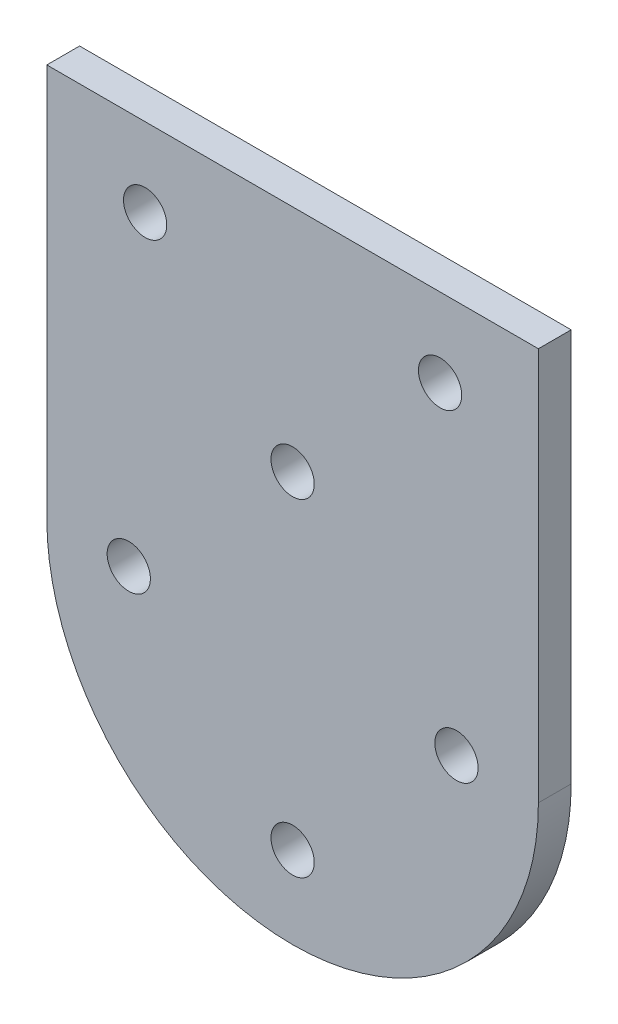
SolidWorks part; units mm, degrees
ref_plane "Front Plane" through (0, 0, 0) normal (0, 0, 1) x (1, 0, 0)
ref_plane "Top Plane" through (0, 0, 0) normal (0, 1, 0) x (1, 0, 0)
ref_plane "Right Plane" through (0, 0, 0) normal (1, 0, 0) x (0, 0, -1)
sketch "Sketch6" plane through (0, 0, 0) normal (0, 0, 1) x (1, 0, 0)
  line L0 (0, 0) -> (62.1656, 0) construction
  line L4 (-62.1656, 0) -> (0, 0) construction
  line L12 (0, -3.292) -> (0, 175) construction
  line L13 (37.5, 0) -> (37.5, 60)
  line L14 (37.5, 60) -> (-37.5, 60)
  line L15 (-37.5, 60) -> (-37.5, 0)
  arc A2 (-37.5, 0) -> (37.5, 0) centre (0, 0) ccw
  arc A7 (-37.5, 0) -> (37.5, 0) centre (0, 0) ccw
  dimension "D4" = 75
  dimension "D5" = 60
extrude "Boss-Extrude1" add sketch "Sketch6" along normal blind 5
sketch "Sketch7" plane through (0, 0, 0) normal (0, 0, -1) x (-1, 0, 0)
  line L1 (-37.5, 60) -> (-22.5, 60) construction
  line L2 (-37.5, 60) -> (-37.5, 48) construction
  line L3 (-37.5, 48) -> (-22.5, 48) construction
  line L4 (-22.5, 60) -> (-22.5, 48) construction
  line L5 (37.5, 60) -> (22.5, 60) construction
  line L6 (37.5, 60) -> (37.5, 48) construction
  line L7 (37.5, 48) -> (22.5, 48) construction
  line L8 (22.5, 60) -> (22.5, 48) construction
  circle A0 centre (0, 0) radius 25 construction
  circle A1 centre (0, 0) radius 37.73 construction
  dimension "D1" = 50
  dimension "D2" = 15
  dimension "D3" = 12
hole_wizard "M6 Clearance Hole2" positions "Sketch10" profile "Sketch11" hole size "M6" standard "ANSI Metric" end condition through all
sketch "Sketch10" plane through (0, 0, 0) normal (0, 0, -1) x (-1, 0, 0)
  circle A0 centre (0, 0) radius 25 construction
  point P0 (-22.5, 48)
  point P3 (22.5, 48)
  point P6 (0, 25)
  point P10 (25, 0)
  point P12 (0, -25)
  point P14 (-25, 0)
sketch "Sketch11" plane through (22.5, 48, 0) normal (1, 0, 0) x (0, 1, 0)
  line L0 (0, 0) -> (0, 5)
  line L1 (0, 5) -> (3.3, 5)
  line L2 (3.3, 5) -> (3.3, 0.025)
  line L3 (3.3, 0.025) -> (3.325, 0)
  line L5 (3.325, 0) -> (0, 0)
  line L6 (-3.3, 0.025) -> (-3.325, 0) construction
  line L11 (0, -6.35) -> (0, 107.95) construction
  dimension "Thru Hole Dia." = 6.6
  dimension "Thru Hole Depth" = 5
  dimension "Near C'Sink Dia." = 6.65
  dimension "Near C'Sink Angle" = 90
